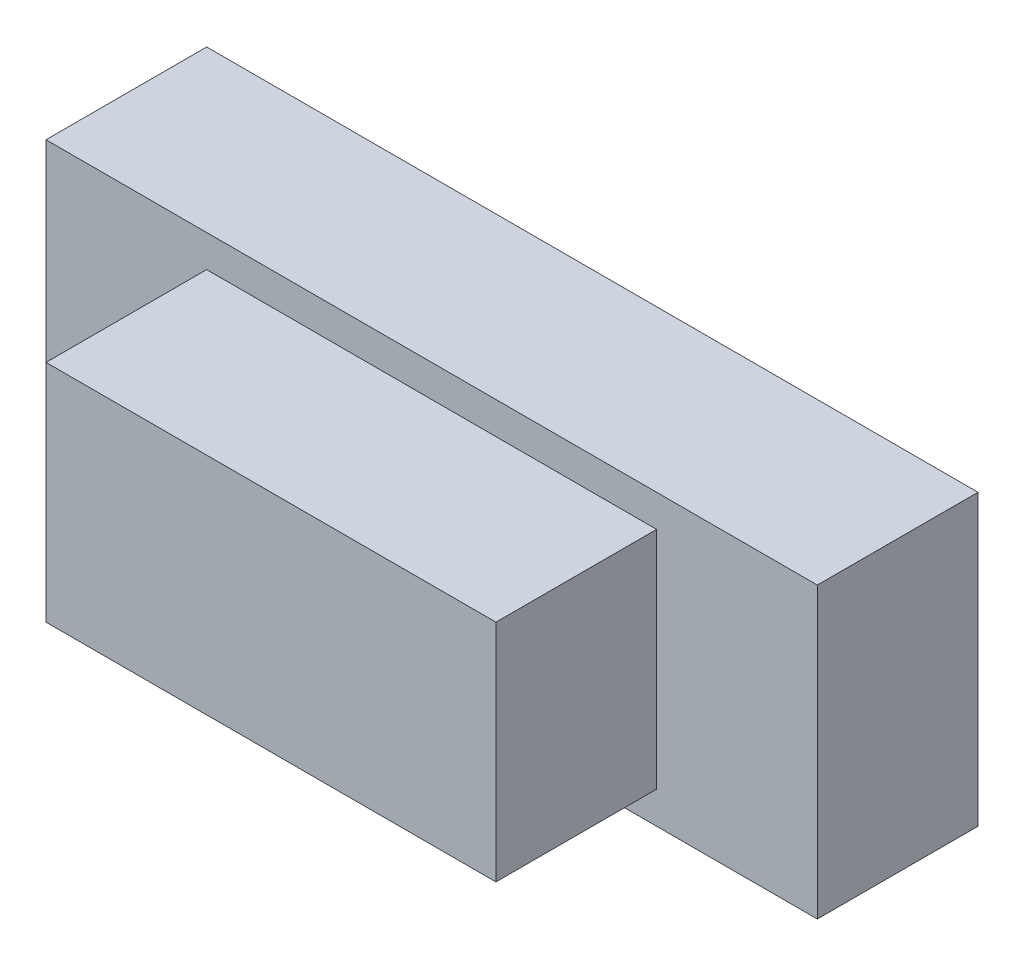
SolidWorks part; units mm, degrees
ref_plane "Front Plane" through (0, 0, 0) normal (0, 0, 1) x (1, 0, 0)
ref_plane "Top Plane" through (0, 0, 0) normal (0, 1, 0) x (1, 0, 0)
ref_plane "Right Plane" through (0, 0, 0) normal (1, 0, 0) x (0, 0, -1)
sketch "Sketch1" plane through (0, 0, 0) normal (0, 0, 1) x (1, 0, 0)
  line L0 (-30.48, 0) -> (30.48, 0) construction
  line L1 (30.48, 11.43) -> (-30.48, 11.43)
  line L2 (30.48, 11.43) -> (30.48, -11.43)
  line L3 (30.48, -11.43) -> (-30.48, -11.43)
  line L4 (-30.48, 11.43) -> (-30.48, -11.43)
  dimension "D1" = 60.96
  dimension "D2" = 22.86
extrude "Boss-Extrude1" add sketch "Sketch1" along normal blind 12.7
sketch "Sketch2" plane through (0, 0, 12.7) normal (0, 0, 1) x (1, 0, 0)
  line L1 (17.78, 8.89) -> (-17.78, 8.89)
  line L2 (17.78, 8.89) -> (17.78, -8.89)
  line L3 (17.78, -8.89) -> (-17.78, -8.89)
  line L4 (-17.78, 8.89) -> (-17.78, -8.89)
  line L5 (17.78, 8.89) -> (-17.78, -8.89) construction
  line L6 (17.78, -8.89) -> (-17.78, 8.89) construction
  point P0 (0, 0)
  dimension "D1" = 35.56
  dimension "D2" = 17.78
extrude "Teensy" add sketch "Sketch2" along normal blind 12.7
